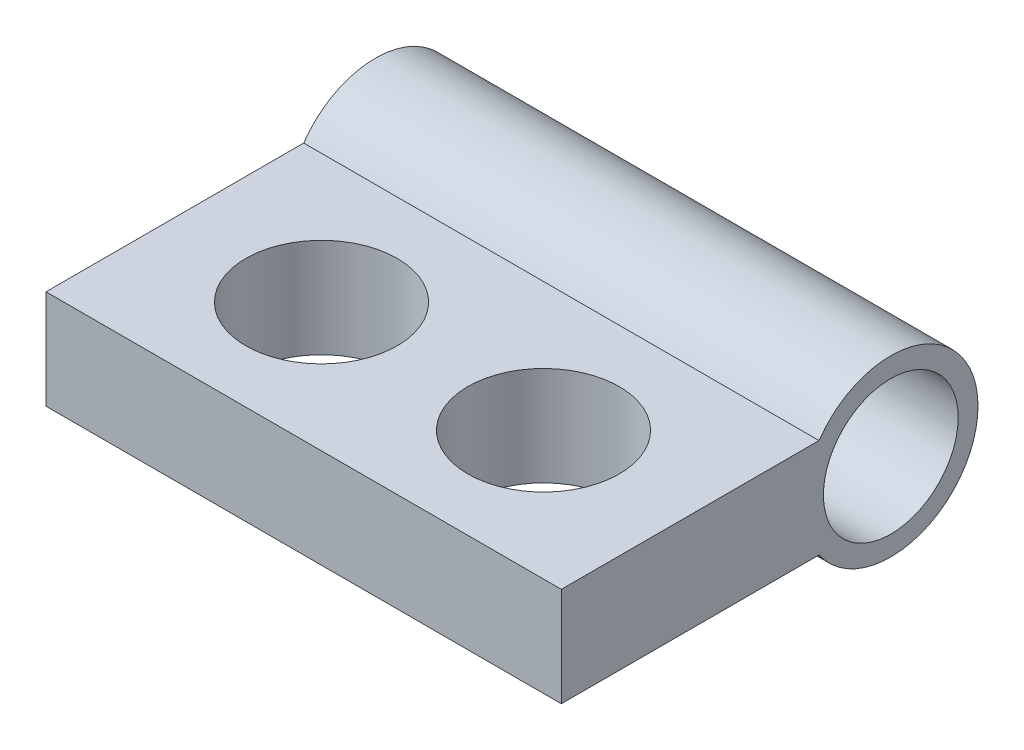
SolidWorks part; units mm, degrees
ref_plane "Front Plane" through (0, 0, 0) normal (0, 0, 1) x (1, 0, 0)
ref_plane "Top Plane" through (0, 0, 0) normal (0, 1, 0) x (1, 0, 0)
ref_plane "Right Plane" through (0, 0, 0) normal (1, 0, 0) x (0, 0, -1)
sketch "Sketch1" plane through (0, 0, 0) normal (0, 1, 0) x (1, 0, 0)
  line L0 (0, 87.1988) -> (0, -83.1649) construction
  line L2 (-41.275, -20.6375) -> (41.275, -20.6375)
  line L3 (-41.275, -20.6375) -> (-41.275, 20.6375)
  line L4 (-41.275, 20.6375) -> (41.275, 20.6375)
  line L5 (41.275, -20.6375) -> (41.275, 20.6375)
  line L6 (-41.275, -20.6375) -> (41.275, 20.6375) construction
  line L7 (-41.275, 20.6375) -> (41.275, -20.6375) construction
  circle A0 centre (17.78, 0) radius 12.1285
  circle A1 centre (-17.78, 0) radius 12.1285
  point P7 (0, 0)
  dimension "D1" = 24.257
  dimension "D2" = 35.56
  dimension "D3" = 82.55
  dimension "D4" = 41.275
extrude "Boss-Extrude1" add sketch "Sketch1" along normal blind 15.875
sketch "Sketch2" plane through (41.275, 0, 0) normal (1, 0, 0) x (0, 0, -1)
  line L0 (-28.4627, 7.9375) -> (32.1335, 7.9375) construction
  line L1 (20.6375, 15.875) -> (20.6375, 0) construction
  circle A0 centre (32.1335, 7.9375) radius 10.795
  circle A1 centre (32.1335, 7.9375) radius 13.97
  point P4 (20.6375, 7.9375)
  dimension "D1" = 21.59
  dimension "D2" = 3.175
extrude "Boss-Extrude2" add sketch "Sketch2" against normal up to surface (82.55 mm away) up to face at (-41.275, 7.9375, 0)
equation "\"D1@Sketch1\"=0.945in + 0.01in"
equation "\"D1@Sketch2\"=0.84in + 0.01in"
